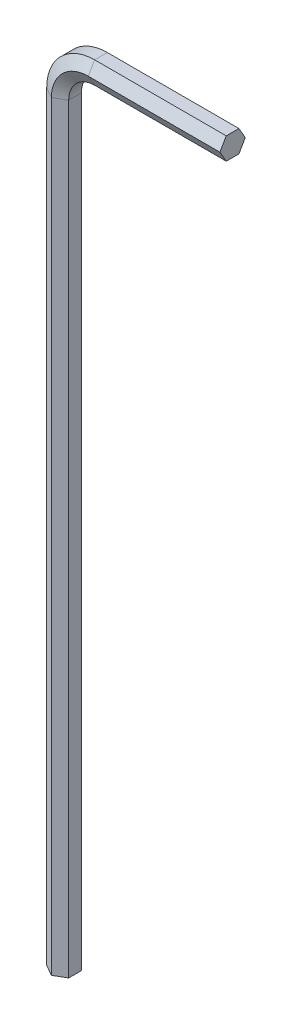
SolidWorks part; units mm, degrees
other "Defeature"
material "Plain Carbon Steel"
ref_plane "Front Plane" through (0, 0, 0) normal (0, 0, 1) x (1, 0, 0)
ref_plane "Top Plane" through (0, 0, 0) normal (0, 1, 0) x (1, 0, 0)
ref_plane "Right Plane" through (0, 0, 0) normal (1, 0, 0) x (0, 0, -1)
sketch "Sketch1" plane through (0, 0, 0) normal (0, 0, 1) x (1, 0, 0)
  line L0 (0, 0) -> (0, 82.31)
  line L1 (4, 86.31) -> (18.25, 86.31)
  arc A0 (0, 82.31) -> (4, 86.31) centre (4, 82.31) cw
  point P8 (0, 86.31)
  dimension "D4" = 4
  dimension "D1" = 86.31
  dimension "D3" = 18.25
sketch "Sketch2" plane through (0, 0, 0) normal (0, 1, 0) x (1, 0, 0)
  line L1 (0, 1.3741) -> (-1.19, 0.687)
  line L2 (-1.19, 0.687) -> (-1.19, -0.687)
  line L3 (-1.19, -0.687) -> (0, -1.3741)
  line L4 (0, -1.3741) -> (1.19, -0.687)
  line L5 (1.19, -0.687) -> (1.19, 0.687)
  line L6 (1.19, 0.687) -> (0, 1.3741)
  circle A0 centre (0, 0) radius 1.19 construction
  dimension "D1" = 2.38
sweep "Sweep1" add profiles "Sketch2" path "Sketch1"
